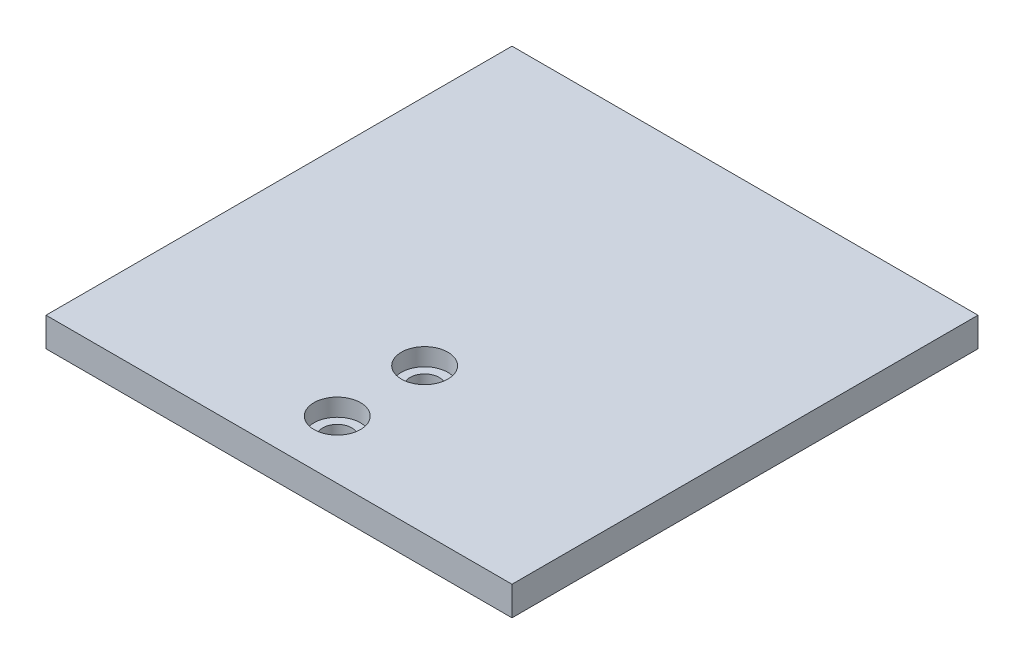
SolidWorks part; units mm, degrees
ref_plane "Front Plane" through (0, 0, 0) normal (0, 0, 1) x (1, 0, 0)
ref_plane "Top Plane" through (0, 0, 0) normal (0, 1, 0) x (1, 0, 0)
ref_plane "Right Plane" through (0, 0, 0) normal (1, 0, 0) x (0, 0, -1)
sketch "Sketch1" plane through (0, 0, 0) normal (0, 1, 0) x (1, 0, 0)
  line L1 (40, -40) -> (-40, -40)
  line L2 (40, -40) -> (40, 40)
  line L3 (40, 40) -> (-40, 40)
  line L4 (-40, -40) -> (-40, 40)
  line L5 (40, -40) -> (-40, 40) construction
  line L6 (40, 40) -> (-40, -40) construction
  point P0 (0, 0)
extrude "Boss-Extrude1" add sketch "Sketch1" along normal blind 5
sketch "Sketch2" plane through (0, 5, 0) normal (0, 1, 0) x (1, 0, 0)
  circle A0 centre (0, -15) radius 2.5
  circle A1 centre (0, -30) radius 2.5
extrude "Cut-Extrude1" cut sketch "Sketch2" against normal blind 15
sketch "Sketch3" plane through (0, 5, 0) normal (0, 1, 0) x (1, 0, 0)
  circle A0 centre (0, -15) radius 4
  circle A1 centre (0, -30) radius 4
extrude "Cut-Extrude2" cut sketch "Sketch3" against normal blind 3
